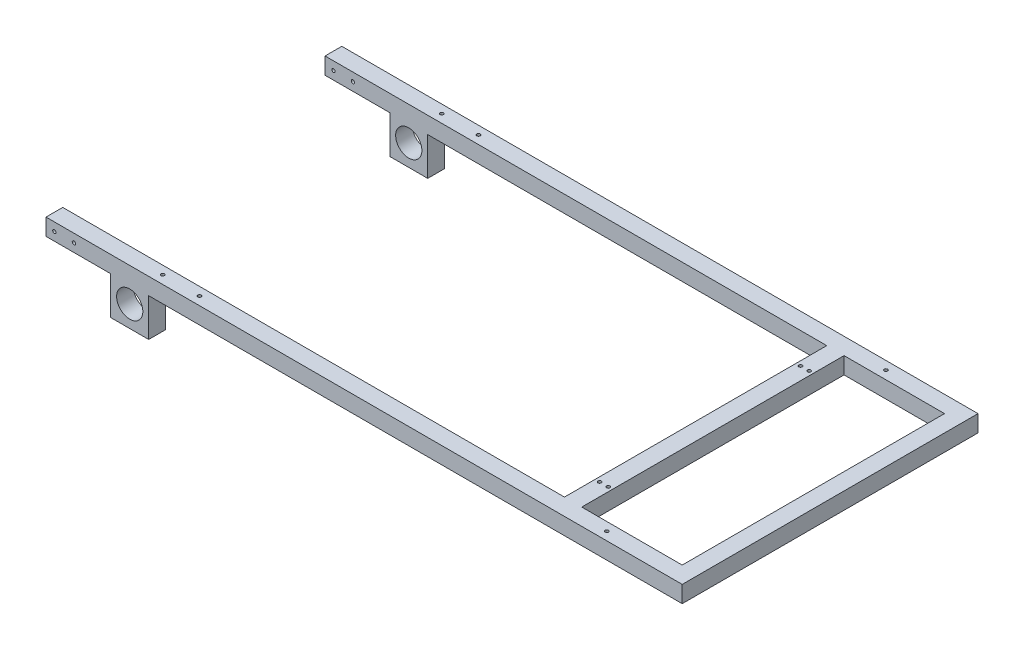
SolidWorks part; units mm, degrees
ref_plane "前视基准面" through (0, 0, 0) normal (0, 0, 1) x (1, 0, 0)
ref_plane "上视基准面" through (0, 0, 0) normal (0, 1, 0) x (1, 0, 0)
ref_plane "右视基准面" through (0, 0, 0) normal (1, 0, 0) x (0, 0, -1)
sketch "草图1" plane through (0, 0, 0) normal (0, 1, 0) x (1, 0, 0)
  line L1 (-990, 265) -> (990, 265)
  line L2 (-990, 265) -> (-990, -265)
  line L3 (-990, -265) -> (990, -265)
  line L4 (990, 265) -> (990, -265)
  line L5 (-990, 265) -> (990, -265) construction
  line L6 (-990, -265) -> (990, 265) construction
  line L7 (-960, 235) -> (960, 235)
  line L8 (-960, 235) -> (-960, -235)
  line L9 (-960, -235) -> (960, -235)
  line L10 (960, 235) -> (960, -235)
  line L11 (-960, 235) -> (960, -235) construction
  line L12 (-960, -235) -> (960, 235) construction
  point P0 (0, 0)
  point P6 (0, 0)
  dimension "D1" = 1980
  dimension "D2" = 530
  dimension "D3" = 30
  dimension "D4" = 30
extrude "凸台-拉伸1" add sketch "草图1" along normal blind 30
sketch "草图2" plane through (0, 0, 0) normal (0, -1, 0) x (1, 0, 0)
  line L0 (0, 439.6423) -> (0, -491.4203) construction
  line L1 (-990, 265) -> (990, 265) construction
  line L2 (-34, 265) -> (34, 265)
  line L3 (-34, 265) -> (-34, 235)
  line L4 (-34, 235) -> (34, 235)
  line L5 (34, 265) -> (34, 235)
  line L6 (-960, 235) -> (960, 235) construction
  line L7 (960, -235) -> (-960, -235) construction
  line L8 (-34, -235) -> (34, -235)
  line L9 (-34, -235) -> (-34, -265)
  line L10 (-34, -265) -> (34, -265)
  line L11 (34, -235) -> (34, -265)
  line L12 (990, -265) -> (-990, -265) construction
  dimension "D1" = 68
  dimension "D2" = 34
  dimension "D3" = 68
  dimension "D4" = 34
extrude "凸台-拉伸2" add sketch "草图2" along normal blind 68
sketch "草图3" plane through (0, 0, 265) normal (0, 0, 1) x (1, 0, 0)
  line L0 (34, -68) -> (-34, -68) construction
  circle A0 centre (0, -30) radius 23.5
  dimension "D1" = 47
  dimension "D2" = 38
extrude "切除-拉伸1" cut sketch "草图3" against normal through all
sketch "草图4" plane through (0, 30, 0) normal (0, 1, 0) x (1, 0, 0)
  line L0 (960, 235) -> (-960, 235) construction
  line L1 (749, 235) -> (780, 235)
  line L2 (749, 235) -> (749, -235)
  line L3 (749, -235) -> (780, -235)
  line L4 (780, 235) -> (780, -235)
  line L5 (-960, -235) -> (960, -235) construction
  line L6 (960, -235) -> (960, 235) construction
  dimension "D1" = 31
  dimension "D2" = 180
extrude "凸台-拉伸3" add sketch "草图4" against normal up to surface (30 mm away) up to face at (504.5, 0, 0)
sketch "草图5" plane through (0, 30, 0) normal (0, 1, 0) x (1, 0, 0)
  line L0 (757, 180) -> (772.5, 180) construction
  line L1 (749, 235) -> (749, -235) construction
  line L2 (780, -235) -> (780, 235) construction
  line L3 (-200.9007, 0) -> (293.2172, 0) construction
  circle A0 centre (757, 180) radius 3
  circle A1 centre (772.5, 180) radius 3
  circle A2 centre (757, -180) radius 3
  circle A3 centre (772.5, -180) radius 3
  dimension "D1" = 6
  dimension "D2" = 6
  dimension "D3" = 8
  dimension "D4" = 7.5
  dimension "D5" = 180
extrude "切除-拉伸2" cut sketch "草图5" against normal through all
sketch "草图6" plane through (0, 30, 0) normal (0, 1, 0) x (1, 0, 0)
  line L0 (900.6933, -265) -> (900.6933, -235) construction
  line L1 (-990, -265) -> (990, -265) construction
  line L2 (780, -235) -> (960, -235) construction
  line L3 (990, -265) -> (990, 265) construction
  circle A0 centre (840, -250) radius 3
  dimension "D1" = 6
  dimension "D2" = 150
extrude "切除-拉伸3" cut sketch "草图6" against normal through all and the other way through all
mirror "镜向1" about plane through (0, 0, 0) normal (0, 0, 1) of "切除-拉伸3"
sketch "草图7" plane through (0, 0, 265) normal (0, 0, 1) x (1, 0, 0)
  line L0 (0, 221.7951) -> (0, -299.5023) construction
  line L1 (-150, 30) -> (-150, 0)
  line L2 (-990, 30) -> (990, 30) construction
  line L3 (-990, 0) -> (-34, 0) construction
  line L4 (-150, 30) -> (-1067.5253, 30)
  line L5 (-1067.5253, 30) -> (-1067.5253, 0)
  line L6 (-1067.5253, 0) -> (-150, 0)
  dimension "D1" = 150
extrude "切除-拉伸4" cut sketch "草图7" against normal through all
sketch "草图8" plane through (0, 0, 265) normal (0, 0, 1) x (1, 0, 0)
  line L0 (-150, 0) -> (-150, 30) construction
  circle A0 centre (-100, 15) radius 3
  dimension "D1" = 6
  dimension "D2" = 50
extrude "切除-拉伸5" cut sketch "草图8" against normal through all
sketch "草图9" plane through (0, 0, 0) normal (0, -1, 0) x (1, 0, 0)
  circle A0 centre (110, 250) radius 3
  circle A1 centre (44, 250) radius 3
extrude "切除-拉伸6" cut sketch "草图9" against normal through all
mirror "镜向2" about plane through (0, 0, 0) normal (0, 0, 1) of "切除-拉伸6"
sketch "草图10" plane through (0, 0, 265) normal (0, 0, 1) x (1, 0, 0)
  circle A0 centre (-135, 15) radius 3
  circle A1 centre (-100, 15) radius 3 construction
  dimension "D1" = 6
  dimension "D2" = 35
extrude "切除-拉伸7" cut sketch "草图10" against normal through all
